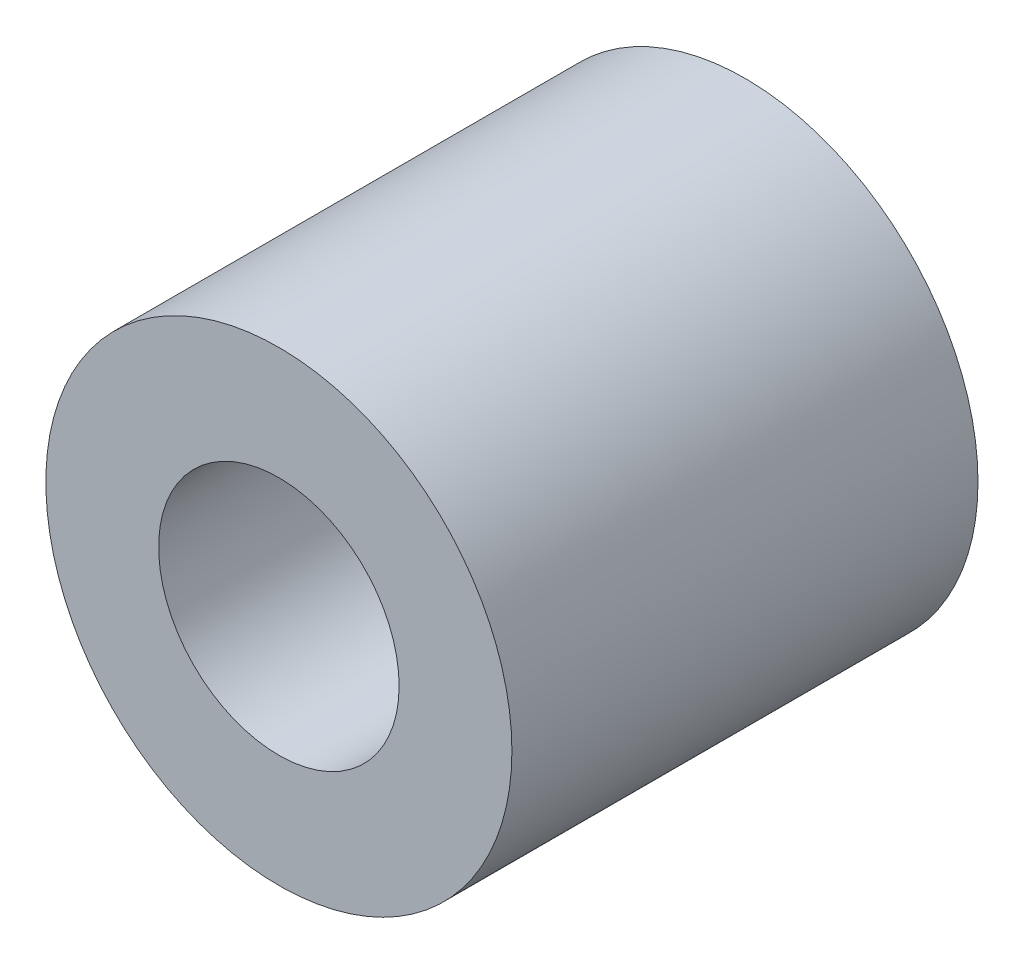
SolidWorks part; units mm, degrees
ref_plane "Front Plane" through (0, 0, 0) normal (0, 0, 1) x (1, 0, 0)
ref_plane "Top Plane" through (0, 0, 0) normal (0, 1, 0) x (1, 0, 0)
ref_plane "Right Plane" through (0, 0, 0) normal (1, 0, 0) x (0, 0, -1)
sketch "Sketch1" plane through (0, 0, 0) normal (0, 0, 1) x (1, 0, 0)
  circle A0 centre (0, 0) radius 3.175
  circle A1 centre (0, 0) radius 1.6383
  dimension "D1" = 6.35
  dimension "ID" = 3.2766
extrude "Extrude1" add sketch "Sketch1" along normal mid plane 6.35
sketch "Sketch2" plane through (0, 0, 0) normal (1, 0, 0) x (0, 0, -1)
  line L0 (-3.175, -1.6383) -> (3.175, -1.6383) construction
  line L3 (3.175, 1.6383) -> (-3.175, 1.6383) construction
  line L5 (-3.175, -1.6383) -> (3.175, -1.6383)
  line L6 (3.175, 1.6383) -> (-3.175, 1.6383)
sketch "Sketch4" plane through (0, 0, 3.175) normal (0, 0, 1) x (1, 0, 0)
  line L0 (0, 0) -> (-1.1585, 1.1585)
  line L1 (0, -6.985) -> (0, 6.985) construction
  circle A0 centre (0, 0) radius 1.6383 construction
  dimension "D1" = 45
